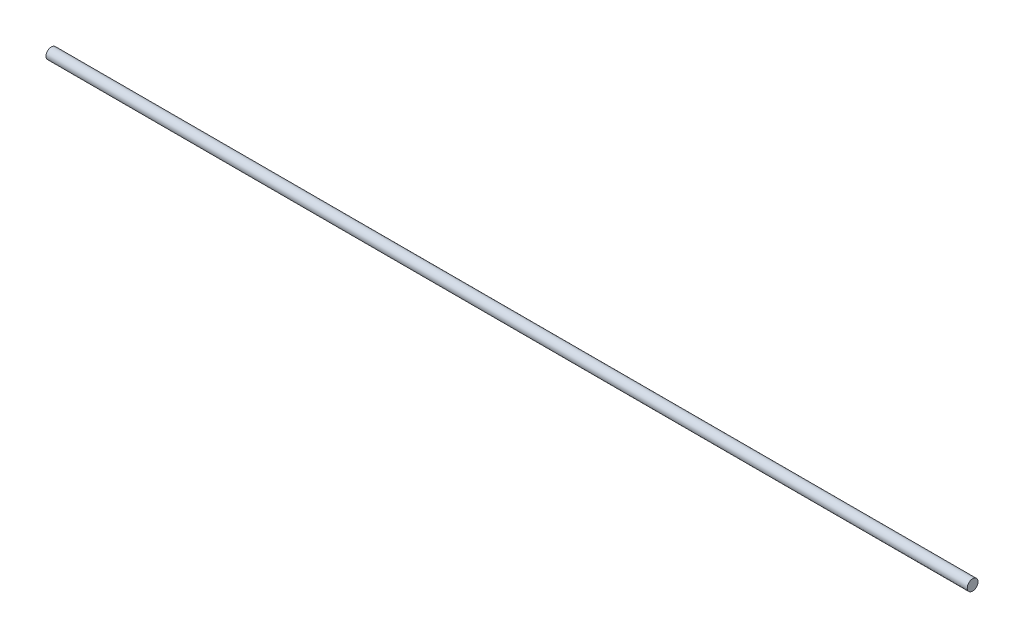
SolidWorks part; units mm, degrees
material "1060 Alloy"
ref_plane "Front Plane" through (0, 0, 0) normal (0, 0, 1) x (1, 0, 0)
ref_plane "Top Plane" through (0, 0, 0) normal (0, 1, 0) x (1, 0, 0)
ref_plane "Right Plane" through (0, 0, 0) normal (1, 0, 0) x (0, 0, -1)
sketch "Sketch1" plane through (0, 0, 0) normal (1, 0, 0) x (0, 0, -1)
  circle A0 centre (0, 0) radius 3.565
extrude "Boss-Extrude1" add sketch "Sketch1" along normal blind 609.6
